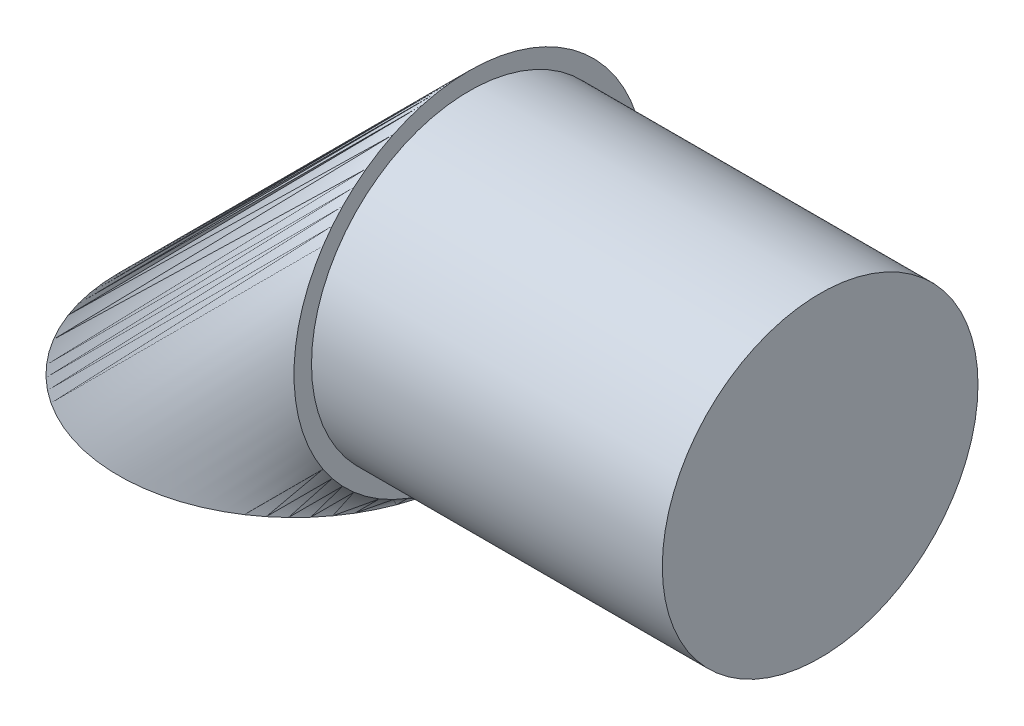
SolidWorks part; units mm, degrees
material "1060 Alloy"
ref_plane "Front Plane" through (0, 0, 0) normal (0, 0, 1) x (1, 0, 0)
ref_plane "Top Plane" through (0, 0, 0) normal (0, 1, 0) x (1, 0, 0)
ref_plane "Right Plane" through (0, 0, 0) normal (1, 0, 0) x (0, 0, -1)
sketch "Sketch2" plane through (0, 0, 0) normal (0, 1, 0) x (1, 0, 0)
  circle A0 centre (0, 0) radius 50
  dimension "D1" = 100
sketch "Sketch4" plane through (0, 0, 0) normal (0, 0, 1) x (1, 0, 0)
  line L0 (50, 0) -> (-50, 0) construction
  line L1 (50, 0) -> (-50, 0) construction
  line L2 (50, 50) -> (50, 0) construction
  arc A0 (0, 0) -> (50, 50) centre (50, 0) cw
sweep "Sweep1" add profiles "Sketch2" path "Sketch4"
sketch "Sketch5" plane through (50, 0, 0) normal (1, 0, 0) x (0, 0, -1)
  circle A0 centre (0, 50) radius 45
  circle A1 centre (0, 50) radius 50
  circle A2 centre (0, 50) radius 50 construction
  dimension "D2" = 90
  dimension "D1" = 0
extrude "Boss-Extrude1" add sketch "Sketch5" along normal blind 100
ref_plane "Plane1" through (50, 0, 0) normal (1, 0, 0) x (0, 0, -1)
ref_plane "Plane2" through (100, 0, 0) normal (1, 0, 0) x (0, 0, -1)
